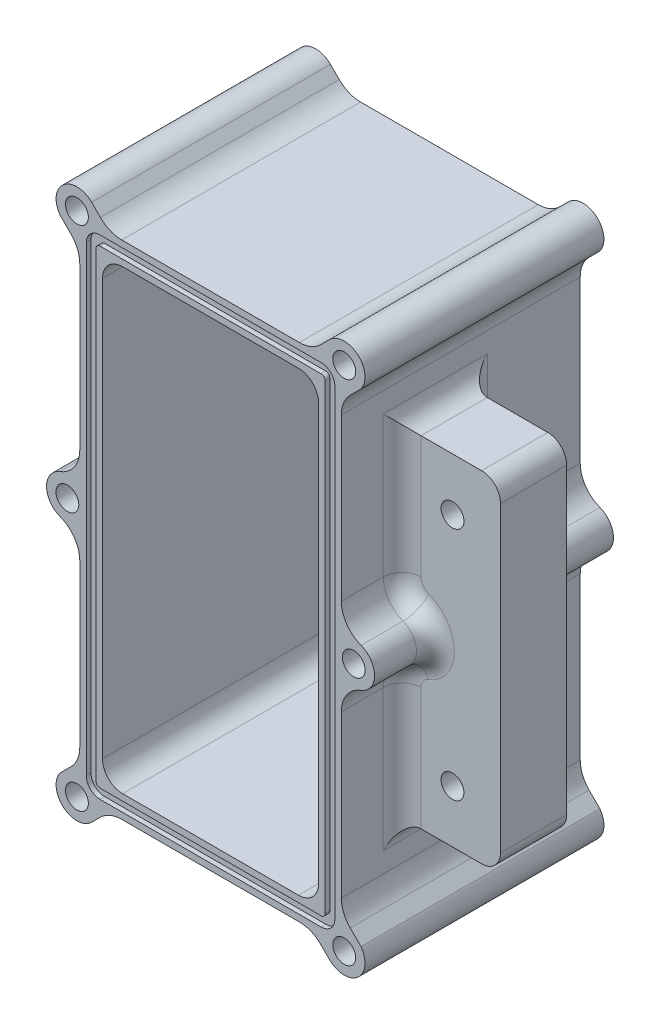
SolidWorks part; units mm, degrees
material "ABS"
ref_plane "X-Y Datum" through (0, 0, 0) normal (0, 0, 1) x (1, 0, 0)
ref_plane "X-Z Datum" through (0, 0, 0) normal (0, 1, 0) x (1, 0, 0)
ref_plane "Y-Z Datum" through (0, 0, 0) normal (1, 0, 0) x (0, 0, -1)
sketch "Sketch2" plane through (0, 0, 0) normal (0, 0, 1) x (1, 0, 0)
  line L1 (-28.575, 60.325) -> (28.575, 60.325)
  line L2 (-28.575, 60.325) -> (-28.575, -60.325)
  line L3 (-28.575, -60.325) -> (28.575, -60.325)
  line L4 (28.575, 60.325) -> (28.575, -60.325)
  line L5 (-28.575, 60.325) -> (28.575, -60.325) construction
  line L6 (-28.575, -60.325) -> (28.575, 60.325) construction
  point P0 (0, 0)
  dimension "D1" = 57.15
  dimension "D2" = 120.65
extrude "Boss-Extrude1" add sketch "Sketch2" along normal mid plane 57.15
shell "Shell1" thickness 6
sketch "Sketch3" plane through (0, 0, -28.575) normal (0, 0, 1) x (1, 0, 0)
  line L4 (28.575, -60.325) -> (28.575, 60.325)
  line L5 (28.575, 60.325) -> (-28.575, 60.325)
  line L6 (-28.575, 60.325) -> (-28.575, -60.325)
  line L7 (-28.575, -60.325) -> (28.575, -60.325)
  line L8 (28.575, -60.325) -> (28.575, 60.325)
  line L9 (28.575, 60.325) -> (-28.575, 60.325)
  line L10 (-28.575, 60.325) -> (-28.575, -60.325)
  line L11 (-28.575, -60.325) -> (28.575, -60.325)
  dimension "D1" = 0
extrude "Cut-Extrude1" cut sketch "Sketch3" against normal blind 50.8
fillet "Fillet1" radius 5.334 8 edges at (-34.575, -66.325, -3) (34.575, -66.325, -3) (34.575, 66.325, -3) (-34.575, 66.325, -3) (-28.575, -60.325, -3) (28.575, -60.325, -3) (-28.575, 60.325, -3) (28.575, 60.325, -3)
sketch "Sketch5" plane through (0, 0, -34.575) normal (0, 0, -1) x (-1, 0, 0)
  line L19 (-29.241, -64.6077) -> (29.241, -64.6077)
  line L20 (32.8577, -60.991) -> (32.8577, 60.991)
  line L21 (29.241, 64.6077) -> (-29.241, 64.6077)
  line L22 (-32.8577, 60.991) -> (-32.8577, -60.991)
  line L23 (-29.241, -63.325) -> (29.241, -63.325)
  line L24 (31.575, -60.991) -> (31.575, 60.991)
  line L25 (29.241, 63.325) -> (-29.241, 63.325)
  line L26 (-31.575, 60.991) -> (-31.575, -60.991)
  line L27 (-29.241, -63.325) -> (29.241, -63.325) construction
  line L28 (31.575, -60.991) -> (31.575, 60.991) construction
  line L29 (29.241, 63.325) -> (-29.241, 63.325) construction
  line L30 (-31.575, 60.991) -> (-31.575, -60.991) construction
  line L31 (-30.2923, 60.991) -> (-30.2923, -60.991)
  line L32 (-29.241, -62.0423) -> (29.241, -62.0423)
  line L33 (30.2923, -60.991) -> (30.2923, 60.991)
  line L34 (29.241, 62.0423) -> (-29.241, 62.0423)
  arc A17 (29.241, -64.6077) -> (32.8577, -60.991) centre (29.241, -60.991) ccw
  arc A18 (32.8577, 60.991) -> (29.241, 64.6077) centre (29.241, 60.991) ccw
  arc A19 (-29.241, 64.6077) -> (-32.8577, 60.991) centre (-29.241, 60.991) ccw
  arc A20 (-32.8577, -60.991) -> (-29.241, -64.6077) centre (-29.241, -60.991) ccw
  arc A21 (-31.575, -60.991) -> (-29.241, -63.325) centre (-29.241, -60.991) ccw
  arc A22 (29.241, -63.325) -> (31.575, -60.991) centre (29.241, -60.991) ccw
  arc A23 (31.575, 60.991) -> (29.241, 63.325) centre (29.241, 60.991) ccw
  arc A24 (-29.241, 63.325) -> (-31.575, 60.991) centre (-29.241, 60.991) ccw
  arc A25 (-31.575, -60.991) -> (-29.241, -63.325) centre (-29.241, -60.991) ccw construction
  arc A26 (29.241, -63.325) -> (31.575, -60.991) centre (29.241, -60.991) ccw construction
  arc A27 (31.575, 60.991) -> (29.241, 63.325) centre (29.241, 60.991) ccw construction
  arc A28 (-29.241, 63.325) -> (-31.575, 60.991) centre (-29.241, 60.991) ccw construction
  arc A29 (-29.241, 62.0423) -> (-30.2923, 60.991) centre (-29.241, 60.991) ccw
  arc A30 (-30.2923, -60.991) -> (-29.241, -62.0423) centre (-29.241, -60.991) ccw
  arc A31 (29.241, -62.0423) -> (30.2923, -60.991) centre (29.241, -60.991) ccw
  arc A32 (30.2923, 60.991) -> (29.241, 62.0423) centre (29.241, 60.991) ccw
  dimension "D1" = 3
  dimension "D2" = 1.2827
  dimension "D3" = 1.2827
extrude "Cut-Extrude2" cut sketch "Sketch5" against normal blind 1.2446
ref_plane "Plane1" through (0, 0, -3) normal (0, 0, 1) x (1, 0, 0)
sketch "Sketch6" plane through (0, 0, -34.575) normal (0, 0, -1) x (-1, 0, 0)
  line L0 (29.9844, 61.7344) -> (31.7984, 63.5484)
  line L1 (31.7984, 63.5484) -> (35.3339, 67.0839)
  line L2 (39.7675, 63.8292) -> (34.575, 58.6367)
  line L3 (34.575, 60.991) -> (34.575, -60.991) construction
  line L4 (31.4448, 70.973) -> (26.7968, 66.325)
  line L5 (-29.241, 66.325) -> (29.241, 66.325) construction
  line L10 (-29.241, -66.325) -> (29.241, -66.325)
  line L11 (34.575, -60.991) -> (34.575, 60.991)
  line L12 (29.241, 66.325) -> (-29.241, 66.325)
  line L13 (-34.575, 60.991) -> (-34.575, -60.991)
  line L14 (-29.241, -66.325) -> (29.241, -66.325)
  line L15 (34.575, -60.991) -> (34.575, 60.991)
  line L16 (29.241, 66.325) -> (-29.241, 66.325)
  line L17 (-34.575, 60.991) -> (-34.575, -60.991)
  arc A0 (30.2923, 60.991) -> (29.241, 62.0423) centre (29.241, 60.991) ccw construction
  arc A1 (32.8577, 60.991) -> (29.241, 64.6077) centre (29.241, 60.991) ccw construction
  circle A2 centre (35.3339, 67.0839) radius 3.025
  circle A3 centre (35.3339, 67.0839) radius 5.5
  arc A8 (29.241, -66.325) -> (34.575, -60.991) centre (29.241, -60.991) ccw
  arc A9 (34.575, 60.991) -> (29.241, 66.325) centre (29.241, 60.991) ccw
  arc A10 (-29.241, 66.325) -> (-34.575, 60.991) centre (-29.241, 60.991) ccw
  arc A11 (-34.575, -60.991) -> (-29.241, -66.325) centre (-29.241, -60.991) ccw
  arc A12 (29.241, -66.325) -> (34.575, -60.991) centre (29.241, -60.991) ccw
  arc A13 (34.575, 60.991) -> (29.241, 66.325) centre (29.241, 60.991) ccw
  arc A14 (-29.241, 66.325) -> (-34.575, 60.991) centre (-29.241, 60.991) ccw
  arc A15 (-34.575, -60.991) -> (-29.241, -66.325) centre (-29.241, -60.991) ccw
  dimension "D1" = 6.05
  dimension "D2" = 11
  dimension "D3" = 5
  dimension "D4" = 0
extrude "Boss-Extrude2" add sketch "Sketch6" against normal up to surface (63.15 mm away)
sketch "Sketch7" plane through (0, 0, -34.575) normal (0, 0, -1) x (-1, 0, 0)
  line L0 (31.4448, 70.973) -> (26.7968, 66.325) construction
  line L1 (39.7675, 63.8292) -> (34.575, 58.6367) construction
  line L2 (29.9844, 61.7344) -> (31.7984, 63.5484) construction
  line L3 (31.7984, 63.5484) -> (35.3339, 67.0839) construction
  line L4 (-34.575, 60.991) -> (-34.575, -60.991)
  line L5 (-29.241, -66.325) -> (29.241, -66.325)
  line L6 (34.575, -60.991) -> (34.575, 60.991)
  line L7 (29.241, 66.325) -> (-29.241, 66.325)
  line L8 (-34.575, 60.991) -> (-34.575, -60.991)
  line L9 (-29.241, -66.325) -> (29.241, -66.325)
  line L10 (34.575, -60.991) -> (34.575, 60.991)
  line L11 (29.241, 66.325) -> (-29.241, 66.325)
  line L12 (31.4448, 70.973) -> (26.7968, 66.325)
  line L13 (39.7675, 63.8292) -> (34.575, 58.6367)
  line L14 (29.9844, 61.7344) -> (31.7984, 63.5484)
  line L15 (31.7984, 63.5484) -> (35.3339, 67.0839)
  circle A1 centre (35.3339, 67.0839) radius 5.5
  circle A2 centre (35.3339, 67.0839) radius 5.5
  circle A3 centre (35.3339, 67.0839) radius 3.025
  circle A4 centre (35.3339, 67.0839) radius 3.025
  arc A8 (-34.575, -60.991) -> (-29.241, -66.325) centre (-29.241, -60.991) ccw
  arc A9 (29.241, -66.325) -> (34.575, -60.991) centre (29.241, -60.991) ccw
  arc A10 (34.575, 60.991) -> (29.241, 66.325) centre (29.241, 60.991) ccw
  arc A11 (-29.241, 66.325) -> (-34.575, 60.991) centre (-29.241, 60.991) ccw
  arc A12 (-34.575, -60.991) -> (-29.241, -66.325) centre (-29.241, -60.991) ccw
  arc A13 (29.241, -66.325) -> (34.575, -60.991) centre (29.241, -60.991) ccw
  arc A14 (34.575, 60.991) -> (29.241, 66.325) centre (29.241, 60.991) ccw
  arc A15 (-29.241, 66.325) -> (-34.575, 60.991) centre (-29.241, 60.991) ccw
  dimension "D1" = 0
  dimension "D2" = 0
  dimension "D3" = 0
extrude "Cut-Extrude3" cut sketch "Sketch7" against normal blind 10
mirror "Mirror2" about plane through (0, 0, 0) normal (1, 0, 0) of "Cut-Extrude3", "Boss-Extrude2"
mirror "Mirror3" about plane through (0, 0, 0) normal (0, 1, 0) of "Mirror2", "Boss-Extrude2", "Cut-Extrude3"
sketch "Sketch8" plane through (0, 0, -34.575) normal (0, 0, -1) x (-1, 0, 0)
  line L0 (32.8577, 0) -> (34.575, 0)
  line L1 (32.8577, -60.991) -> (32.8577, 60.991) construction
  line L2 (34.575, 58.6367) -> (34.575, -58.6367) construction
  line L3 (34.575, 0) -> (37.8577, 0)
  line L4 (32.8577, -60.991) -> (32.8577, 60.991) construction
  line L5 (37.8577, 5.5) -> (34.575, 5.5)
  line L6 (37.8577, -5.5) -> (34.575, -5.5)
  line L7 (34.575, 58.6367) -> (34.575, -58.6367)
  circle A0 centre (37.8577, 0) radius 3.025
  circle A1 centre (37.8577, 0) radius 5.5
  dimension "D1" = 6.05
  dimension "D2" = 11
  dimension "D3" = 5
extrude "Boss-Extrude3" add sketch "Sketch8" against normal up to surface (63.15 mm away)
sketch "Sketch9" plane through (0, 0, -34.575) normal (0, 0, -1) x (-1, 0, 0)
  line L0 (34.575, 58.6367) -> (34.575, -58.6367) construction
  line L1 (37.8577, -5.5) -> (34.575, -5.5) construction
  line L2 (37.8577, 5.5) -> (34.575, 5.5) construction
  line L3 (32.8577, 0) -> (34.575, 0) construction
  line L4 (34.575, 0) -> (37.8577, 0) construction
  line L5 (34.575, 58.6367) -> (34.575, -58.6367)
  line L6 (37.8577, -5.5) -> (34.575, -5.5)
  line L7 (37.8577, 5.5) -> (34.575, 5.5)
  line L8 (32.8577, 0) -> (34.575, 0)
  line L9 (34.575, 0) -> (37.8577, 0)
  circle A1 centre (37.8577, 0) radius 5.5
  circle A2 centre (37.8577, 0) radius 5.5
  circle A3 centre (37.8577, 0) radius 3.025
  circle A4 centre (37.8577, 0) radius 3.025
  dimension "D1" = 0
  dimension "D2" = 0
extrude "Cut-Extrude4" cut sketch "Sketch9" against normal blind 10
mirror "Mirror4" about plane through (0, 0, 0) normal (1, 0, 0) of "Cut-Extrude4", "Boss-Extrude3"
mirror "Mirror6" about plane through (0, 0, -3) normal (0, 0, 1) of "Cut-Extrude2"
sketch "Sketch10" plane through (0, 0, 28.575) normal (0, 0, 1) x (1, 0, 0)
  line L0 (-29.9844, 61.7344) -> (-31.7984, 63.5484) construction
  line L1 (-31.7984, 63.5484) -> (-35.3339, 67.0839) construction
  line L2 (-31.4448, 70.973) -> (-26.7968, 66.325) construction
  line L3 (-39.7675, 63.8292) -> (-34.575, 58.6367) construction
  line L4 (-34.575, 60.991) -> (-34.575, -60.991)
  line L5 (-29.241, -66.325) -> (29.241, -66.325)
  line L6 (34.575, -60.991) -> (34.575, 60.991)
  line L7 (29.241, 66.325) -> (-29.241, 66.325)
  line L8 (-34.575, 60.991) -> (-34.575, -60.991)
  line L9 (-29.241, -66.325) -> (29.241, -66.325)
  line L10 (34.575, -60.991) -> (34.575, 60.991)
  line L11 (29.241, 66.325) -> (-29.241, 66.325)
  line L12 (-29.9844, 61.7344) -> (-31.7984, 63.5484)
  line L13 (-31.7984, 63.5484) -> (-35.3339, 67.0839)
  line L14 (-31.4448, 70.973) -> (-26.7968, 66.325)
  line L15 (-39.7675, 63.8292) -> (-34.575, 58.6367)
  circle A1 centre (-35.3339, 67.0839) radius 3.025
  circle A2 centre (-35.3339, 67.0839) radius 3.025
  circle A3 centre (-35.3339, 67.0839) radius 5.5
  circle A4 centre (-35.3339, 67.0839) radius 5.5
  arc A8 (-34.575, -60.991) -> (-29.241, -66.325) centre (-29.241, -60.991) ccw
  arc A9 (29.241, -66.325) -> (34.575, -60.991) centre (29.241, -60.991) ccw
  arc A10 (34.575, 60.991) -> (29.241, 66.325) centre (29.241, 60.991) ccw
  arc A11 (-29.241, 66.325) -> (-34.575, 60.991) centre (-29.241, 60.991) ccw
  arc A12 (-34.575, -60.991) -> (-29.241, -66.325) centre (-29.241, -60.991) ccw
  arc A13 (29.241, -66.325) -> (34.575, -60.991) centre (29.241, -60.991) ccw
  arc A14 (34.575, 60.991) -> (29.241, 66.325) centre (29.241, 60.991) ccw
  arc A15 (-29.241, 66.325) -> (-34.575, 60.991) centre (-29.241, 60.991) ccw
  dimension "D1" = 0
  dimension "D2" = 0
  dimension "D3" = 0
extrude "Cut-Extrude5" cut sketch "Sketch10" against normal blind 10
mirror "Mirror9" about plane through (0, 0, 0) normal (1, 0, 0) of "Cut-Extrude5"
mirror "Mirror10" about plane through (0, 0, 0) normal (0, 1, 0) of "Mirror9", "Cut-Extrude5"
sketch "Sketch11" plane through (0, 0, 28.575) normal (0, 0, 1) x (1, 0, 0)
  line L0 (-32.8577, 0) -> (-34.575, 0) construction
  line L1 (-34.575, 0) -> (-37.8577, 0) construction
  line L2 (-37.8577, 5.5) -> (-34.575, 5.5) construction
  line L3 (-37.8577, -5.5) -> (-34.575, -5.5) construction
  line L4 (-34.575, 58.6367) -> (-34.575, -58.6367) construction
  line L5 (-32.8577, 0) -> (-34.575, 0)
  line L6 (-34.575, 0) -> (-37.8577, 0)
  line L7 (-37.8577, 5.5) -> (-34.575, 5.5)
  line L8 (-37.8577, -5.5) -> (-34.575, -5.5)
  line L9 (-34.575, 58.6367) -> (-34.575, -58.6367)
  circle A1 centre (-37.8577, 0) radius 3.025
  circle A2 centre (-37.8577, 0) radius 3.025
  circle A3 centre (-37.8577, 0) radius 5.5
  circle A4 centre (-37.8577, 0) radius 5.5
  dimension "D1" = 0
  dimension "D2" = 0
extrude "Cut-Extrude6" cut sketch "Sketch11" against normal blind 10
mirror "Mirror11" about plane through (0, 0, 0) normal (1, 0, 0) of "Cut-Extrude6"
fillet "Fillet2" radius 8 12 edges at (-34.575, 5.5, -3) (-34.575, -5.5, -3) (-34.575, -58.6367, -3) (-26.7968, -66.325, -3) (26.7968, -66.325, -3) (34.575, -58.6367, -3) (34.575, -5.5, -3) (34.575, 5.5, -3) (34.575, 58.6367, -3) (26.7968, 66.325, -3) (-26.7968, 66.325, -3) (-34.575, 58.6367, -3)
ref_plane "Plane2" through (0, 0, -5) normal (0, 0, 1) x (1, 0, 0)
sketch "Sketch13" plane through (0, 0, -5) normal (0, 0, 1) x (1, 0, 0)
  line L0 (60.575, 0) -> (34.575, 0) construction
  line L1 (34.575, -45) -> (60.575, -45)
  line L2 (34.575, -45) -> (34.575, 45)
  line L3 (34.575, 45) -> (60.575, 45)
  line L4 (60.575, -45) -> (60.575, 45)
  line L5 (47.875, -31.075) -> (47.875, 31.075) construction
  line L14 (-23.4831, -66.325) -> (23.4831, -66.325)
  line L15 (-31.4448, -70.973) -> (-29.14, -68.6681)
  line L16 (-36.9181, -60.9798) -> (-39.7675, -63.8292)
  line L17 (-34.575, -12.649) -> (-34.575, -55.323)
  line L18 (-34.575, 55.323) -> (-34.575, 12.649)
  line L19 (-39.7675, 63.8292) -> (-36.9181, 60.9798)
  line L20 (-29.14, 68.6681) -> (-31.4448, 70.973)
  line L21 (23.4831, 66.325) -> (-23.4831, 66.325)
  line L22 (31.4448, 70.973) -> (29.14, 68.6681)
  line L23 (36.9181, 60.9798) -> (39.7675, 63.8292)
  line L24 (34.575, 12.649) -> (34.575, 55.323)
  line L25 (34.575, -55.323) -> (34.575, -12.649)
  line L26 (39.7675, -63.8292) -> (36.9181, -60.9798)
  line L27 (29.14, -68.6681) -> (31.4448, -70.973)
  line L28 (-23.4831, -66.325) -> (23.4831, -66.325)
  line L29 (-31.4448, -70.973) -> (-29.14, -68.6681)
  line L30 (-36.9181, -60.9798) -> (-39.7675, -63.8292)
  line L31 (-34.575, -12.649) -> (-34.575, -55.323)
  line L32 (-34.575, 55.323) -> (-34.575, 12.649)
  line L33 (-39.7675, 63.8292) -> (-36.9181, 60.9798)
  line L34 (-29.14, 68.6681) -> (-31.4448, 70.973)
  line L35 (23.4831, 66.325) -> (-23.4831, 66.325)
  line L36 (31.4448, 70.973) -> (29.14, 68.6681)
  line L37 (36.9181, 60.9798) -> (39.7675, 63.8292)
  line L38 (34.575, 12.649) -> (34.575, 55.323)
  line L39 (34.575, -55.323) -> (34.575, -12.649)
  line L40 (39.7675, -63.8292) -> (36.9181, -60.9798)
  line L41 (29.14, -68.6681) -> (31.4448, -70.973)
  circle A0 centre (47.875, -31.075) radius 3.025
  circle A1 centre (47.875, 31.075) radius 3.025
  arc A18 (-23.4831, -66.325) -> (-29.14, -68.6681) centre (-23.4831, -74.325) ccw
  arc A19 (-39.7675, -63.8292) -> (-31.4448, -70.973) centre (-35.3339, -67.0839) ccw
  arc A20 (-36.9181, -60.9798) -> (-34.575, -55.323) centre (-42.575, -55.323) ccw
  arc A21 (-34.575, -12.649) -> (-39.7796, -5.1533) centre (-42.575, -12.649) ccw
  arc A22 (-39.7796, 5.1533) -> (-39.7796, -5.1533) centre (-37.8577, 0) ccw
  arc A23 (-39.7796, 5.1533) -> (-34.575, 12.649) centre (-42.575, 12.649) ccw
  arc A24 (-34.575, 55.323) -> (-36.9181, 60.9798) centre (-42.575, 55.323) ccw
  arc A25 (-31.4448, 70.973) -> (-39.7675, 63.8292) centre (-35.3339, 67.0839) ccw
  arc A26 (-29.14, 68.6681) -> (-23.4831, 66.325) centre (-23.4831, 74.325) ccw
  arc A27 (23.4831, 66.325) -> (29.14, 68.6681) centre (23.4831, 74.325) ccw
  arc A28 (39.7675, 63.8292) -> (31.4448, 70.973) centre (35.3339, 67.0839) ccw
  arc A29 (36.9181, 60.9798) -> (34.575, 55.323) centre (42.575, 55.323) ccw
  arc A30 (34.575, 12.649) -> (39.7796, 5.1533) centre (42.575, 12.649) ccw
  arc A31 (39.7796, -5.1533) -> (39.7796, 5.1533) centre (37.8577, 0) ccw
  arc A32 (39.7796, -5.1533) -> (34.575, -12.649) centre (42.575, -12.649) ccw
  arc A33 (34.575, -55.323) -> (36.9181, -60.9798) centre (42.575, -55.323) ccw
  arc A34 (31.4448, -70.973) -> (39.7675, -63.8292) centre (35.3339, -67.0839) ccw
  arc A35 (29.14, -68.6681) -> (23.4831, -66.325) centre (23.4831, -74.325) ccw
  arc A36 (-23.4831, -66.325) -> (-29.14, -68.6681) centre (-23.4831, -74.325) ccw
  arc A37 (-39.7675, -63.8292) -> (-31.4448, -70.973) centre (-35.3339, -67.0839) ccw
  arc A38 (-36.9181, -60.9798) -> (-34.575, -55.323) centre (-42.575, -55.323) ccw
  arc A39 (-34.575, -12.649) -> (-39.7796, -5.1533) centre (-42.575, -12.649) ccw
  arc A40 (-39.7796, 5.1533) -> (-39.7796, -5.1533) centre (-37.8577, 0) ccw
  arc A41 (-39.7796, 5.1533) -> (-34.575, 12.649) centre (-42.575, 12.649) ccw
  arc A42 (-34.575, 55.323) -> (-36.9181, 60.9798) centre (-42.575, 55.323) ccw
  arc A43 (-31.4448, 70.973) -> (-39.7675, 63.8292) centre (-35.3339, 67.0839) ccw
  arc A44 (-29.14, 68.6681) -> (-23.4831, 66.325) centre (-23.4831, 74.325) ccw
  arc A45 (23.4831, 66.325) -> (29.14, 68.6681) centre (23.4831, 74.325) ccw
  arc A46 (39.7675, 63.8292) -> (31.4448, 70.973) centre (35.3339, 67.0839) ccw
  arc A47 (36.9181, 60.9798) -> (34.575, 55.323) centre (42.575, 55.323) ccw
  arc A48 (34.575, 12.649) -> (39.7796, 5.1533) centre (42.575, 12.649) ccw
  arc A49 (39.7796, -5.1533) -> (39.7796, 5.1533) centre (37.8577, 0) ccw
  arc A50 (39.7796, -5.1533) -> (34.575, -12.649) centre (42.575, -12.649) ccw
  arc A51 (34.575, -55.323) -> (36.9181, -60.9798) centre (42.575, -55.323) ccw
  arc A52 (31.4448, -70.973) -> (39.7675, -63.8292) centre (35.3339, -67.0839) ccw
  arc A53 (29.14, -68.6681) -> (23.4831, -66.325) centre (23.4831, -74.325) ccw
  point P51 (47.875, 0)
  dimension "D5" = 6.05
  dimension "D2" = 90
  dimension "D3" = 26
  dimension "D4" = 62.15
  dimension "D6" = 12.7
  dimension "D1" = 0
extrude "Boss-Extrude4" add sketch "Sketch13" along normal blind 17.5 contours A49 A50 L2 L1 L4 L3 A48 A1 A0
fillet "Fillet3" radius 5 14 edges at (34.575, -28.8245, 12.5) (36.0037, -8.0863, 12.5) (43.3577, 0, 12.5) (36.0037, 8.0863, 12.5) (34.575, -28.8245, -5) (36.0037, -8.0863, -5) (43.3577, 0, -5) (36.0037, 8.0863, -5) (34.575, -45, 3.75) (34.575, 28.8245, 12.5) (34.575, 45, 3.75) (34.575, 28.8245, -5) (60.575, -45, 3.75) (60.575, 45, 3.75)
